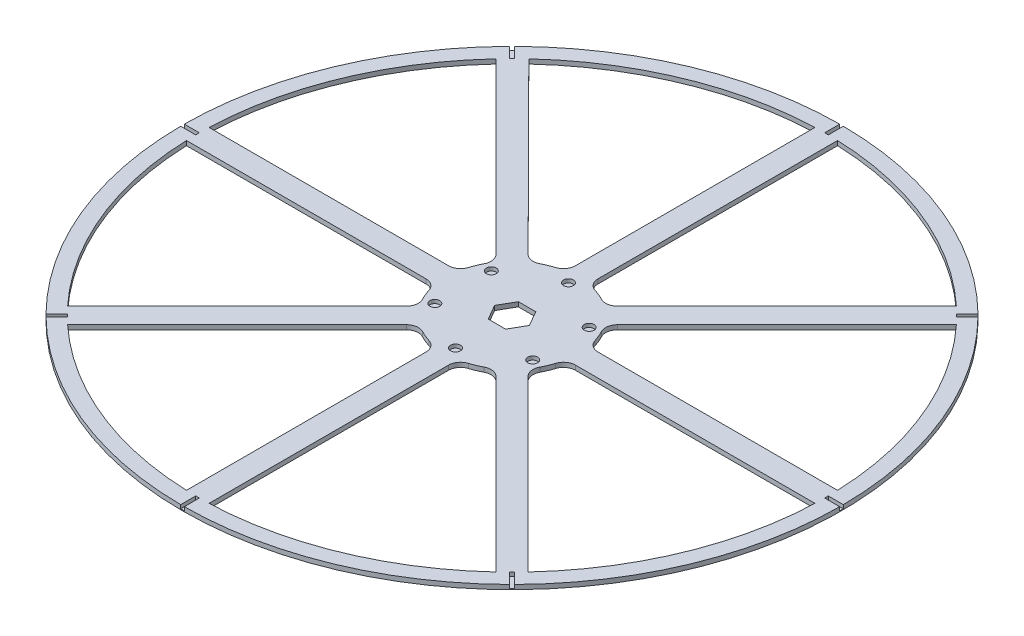
SolidWorks part; units mm, degrees
material "7075-T6, Plate (SS)"
ref_plane "Front Plane" through (0, 0, 0) normal (0, 0, 1) x (1, 0, 0)
ref_plane "Top Plane" through (0, 0, 0) normal (0, 1, 0) x (1, 0, 0)
ref_plane "Right Plane" through (0, 0, 0) normal (1, 0, 0) x (0, 0, -1)
sketch "Sketch1" plane through (0, 0, 0) normal (0, 1, 0) x (1, 0, 0)
  line L0 (4.7625, 132.4707) -> (4.7625, 11.4977)
  line L1 (-4.7625, 132.4707) -> (-4.7625, 11.4977)
  line L2 (-4.7625, 101.5638) -> (4.7625, 101.5638) construction
  line L3 (90.3033, 97.0385) -> (4.7625, 11.4977)
  line L4 (68.4489, 75.1841) -> (75.1841, 68.4489) construction
  line L5 (97.0385, 90.3033) -> (11.4977, 4.7625)
  line L6 (132.4707, 4.7625) -> (11.4977, 4.7625)
  line L7 (101.5638, 4.7625) -> (101.5638, -4.7625) construction
  line L8 (132.4707, -4.7625) -> (11.4977, -4.7625)
  line L9 (97.0385, -90.3033) -> (11.4977, -4.7625)
  line L10 (75.1841, -68.4489) -> (68.4489, -75.1841) construction
  line L11 (90.3033, -97.0385) -> (4.7625, -11.4977)
  line L12 (4.7625, -132.4707) -> (4.7625, -11.4977)
  line L13 (4.7625, -101.5638) -> (-4.7625, -101.5638) construction
  line L14 (-4.7625, -132.4707) -> (-4.7625, -11.4977)
  line L15 (-90.3033, -97.0385) -> (-4.7625, -11.4977)
  line L16 (-68.4489, -75.1841) -> (-75.1841, -68.4489) construction
  line L17 (-97.0385, -90.3033) -> (-11.4977, -4.7625)
  line L18 (-132.4707, -4.7625) -> (-11.4977, -4.7625)
  line L19 (-101.5638, -4.7625) -> (-101.5638, 4.7625) construction
  line L20 (-132.4707, 4.7625) -> (-11.4977, 4.7625)
  line L21 (-97.0385, 90.3033) -> (-11.4977, 4.7625)
  line L22 (-75.1834, 68.4482) -> (-68.3174, 75.3142) construction
  line L23 (-90.1212, 97.2077) -> (-4.7625, 11.4977)
  line L25 (-4.7625, 11.4977) -> (-4.7625, 18.0455)
  line L26 (-11.4977, 4.7625) -> (-17.9605, 4.7625)
  line L28 (-11.4977, -4.7625) -> (-16.0676, -9.3324)
  line L33 (-4.7625, 11.4977) -> (-9.3925, 16.1277)
  line L35 (4.7625, 11.4977) -> (6.6224, 13.3576)
  line L37 (4.7625, 11.4977) -> (4.7625, 18.0455)
  line L39 (11.4977, 4.7625) -> (14.1279, 4.7625)
  line L41 (11.4977, 4.7625) -> (16.1277, 9.3925)
  line L43 (11.4977, -4.7625) -> (13.3576, -6.6224)
  line L45 (11.4977, -4.7625) -> (18.0455, -4.7625)
  line L46 (4.7625, -11.4977) -> (4.7625, -14.1279)
  line L49 (4.7625, -11.4977) -> (9.3925, -16.1277)
  line L50 (-4.7625, -11.4977) -> (-6.6224, -13.3576)
  line L52 (-4.7625, -11.4977) -> (-4.7625, -14.1279)
  line L55 (-11.4977, -4.7625) -> (-14.1279, -4.7625)
  line L57 (-11.4977, 4.7625) -> (-13.3576, 6.6224)
  circle A0 centre (0, 0) radius 138.9062
  arc A2 (-4.7625, 132.4707) -> (-90.1212, 97.2077) centre (0, 0) ccw
  arc A3 (90.3033, 97.0385) -> (4.7625, 132.4707) centre (0, 0) ccw
  arc A4 (132.4707, 4.7625) -> (97.0385, 90.3033) centre (0, 0) ccw
  arc A5 (97.0385, -90.3033) -> (132.4707, -4.7625) centre (0, 0) ccw
  arc A6 (4.7625, -132.4707) -> (90.3033, -97.0385) centre (0, 0) ccw
  arc A7 (-90.3033, -97.0385) -> (-4.7625, -132.4707) centre (0, 0) ccw
  arc A8 (-132.4707, -4.7625) -> (-97.0385, -90.3033) centre (0, 0) ccw
  arc A9 (-97.0385, 90.3033) -> (-132.4707, 4.7625) centre (0, 0) ccw
  point P11 (0, 101.5638)
  point P56 (0, 0)
  dimension "D1" = 277.8125
  dimension "D2" = 9.525
  dimension "D3" = 6.35
  dimension "D4" = 9.525
  dimension "D5" = 9.525
  dimension "D6" = 9.525
  dimension "D7" = 120.9641
  dimension "D8" = 30.8987
  dimension "D9" = 9.71
  dimension "D10" = 30.9068
  dimension "D11" = 30.9068
  dimension "D12" = 9.525
  dimension "D13" = 30.9068
  dimension "D14" = 9.525
  dimension "D15" = 9.525
  dimension "D16" = 30.9068
  dimension "D17" = 9.525
  dimension "D18" = 30.9068
  dimension "D19" = 9.525
  dimension "D20" = 30.9068
  dimension "D21" = 9.525
  dimension "D22" = 30.9068
extrude "Boss-Extrude1" add sketch "Sketch1" along normal blind 1.905 contours A0 A9 L21 L20 A8 L18 L17 A7 L15 L14 A6 L12 L11 A5 L9 L8 A4 L6 L5 A3 L3 L0 A2 L1 L23
sketch "Sketch2" plane through (0, 1.905, 0) normal (0, 1, 0) x (1, 0, 0)
  circle A0 centre (0, 0) radius 27.94
  dimension "D1" = 55.88
extrude "Boss-Extrude2" add sketch "Sketch2" against normal up to surface (1.905 mm away) up to face at (-82.9061, 0, -34.3408)
sketch "Sketch3" plane through (0, 1.905, 0) normal (0, 1, 0) x (1, 0, 0)
  circle A0 centre (0, 0) radius 23.8125 construction
  circle A1 centre (0, 23.8125) radius 2.0828
  circle A2 centre (20.6222, 11.9063) radius 2.0828
  circle A3 centre (20.6222, -11.9062) radius 2.0828
  circle A4 centre (0, -23.8125) radius 2.0828
  circle A5 centre (-20.6222, -11.9063) radius 2.0828
  circle A6 centre (-20.6222, 11.9062) radius 2.0828
  point P17 (0, 0)
  dimension "D1" = 47.625
  dimension "D2" = 4.1656
  dimension "D3" = 6
extrude "Cut-Extrude1" cut sketch "Sketch3" against normal blind 1.524
fillet "Fillet1" radius 5.08 16 edges at (22.835, 0.9525, -16.0998) (-16.0998, 0.9525, 22.835) (4.7625, 0.9525, -27.5311) (4.7625, 0.9525, 27.5311) (16.0998, 0.9525, -22.835) (27.5311, 0.9525, -4.7625) (27.5311, 0.9525, 4.7625) (-27.5311, 0.9525, 4.7625) (22.835, 0.9525, 16.0998) (16.0998, 0.9525, 22.835) (-22.835, 0.9525, -16.0998) (-4.7625, 0.9525, -27.5311) (-4.7625, 0.9525, 27.5311) (-22.835, 0.9525, 16.0998) (-27.5311, 0.9525, -4.7625) (-16.0725, 0.9525, -22.8543)
sketch "Sketch4" plane through (0, 1.905, 0) normal (0, 1, 0) x (1, 0, 0)
  line L1 (-0.762, 138.9062) -> (0.762, 138.9062)
  line L2 (-0.762, 138.9062) -> (-0.762, 132.5563)
  line L3 (-0.762, 132.5563) -> (0.762, 132.5563)
  line L4 (0.762, 138.9062) -> (0.762, 132.5563)
  circle A0 centre (0, 0) radius 138.9062 construction
  point P4 (0, 138.9062)
  dimension "D1" = 1.524
  dimension "D2" = 6.35
extrude "Cut-Extrude2" cut sketch "Sketch4" against normal blind 1.524
pattern_circular "CirPattern1" count 8 every 45 about axis through (0, 0, 0) along (0, 1, 0) of "Cut-Extrude2"
sketch "Sketch5" plane through (0, 1.905, 0) normal (0, 1, 0) x (1, 0, 0)
  line L0 (0, 136.5001) -> (0, -163.2249) construction
  line L7 (217.3388, 0) -> (-227.2686, 0) construction
  line L9 (3.6662, 6.35) -> (-3.6662, 6.35)
  line L10 (-3.6662, 6.35) -> (-7.3323, 0)
  line L11 (-7.3323, 0) -> (-3.6662, -6.35)
  line L12 (-3.6662, -6.35) -> (3.6662, -6.35)
  line L13 (3.6662, -6.35) -> (7.3323, 0)
  line L14 (7.3323, 0) -> (3.6662, 6.35)
  circle A1 centre (0, 0) radius 6.35 construction
  dimension "D1" = 12.7
extrude "Cut-Extrude3" cut sketch "Sketch5" against normal through all
